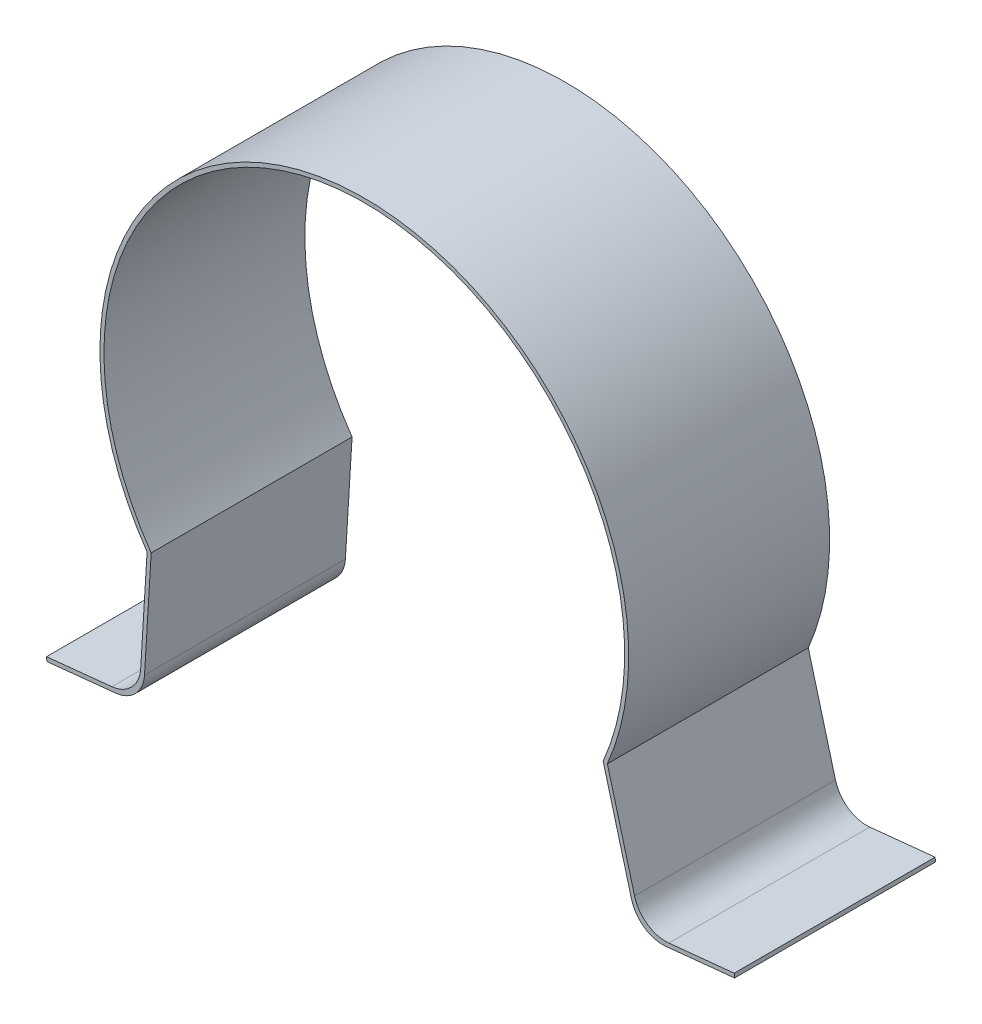
SolidWorks part; units mm, degrees
ref_plane "Спереди" through (0, 0, 0) normal (0, 0, 1) x (1, 0, 0)
ref_plane "Сверху" through (0, 0, 0) normal (0, 1, 0) x (1, 0, 0)
ref_plane "Справа" through (0, 0, 0) normal (1, 0, 0) x (0, 0, -1)
sketch "Эскиз8" plane through (0, 0, 0) normal (0, 0, 1) x (1, 0, 0)
  line L0 (-26.5227, -18.6093) -> (-27.5606, -35.5776)
  line L1 (-27.5606, -35.5776) -> (-39.4981, -36.8007)
  line L2 (0, 31.1118) -> (0, 49.2071) construction
  line L3 (34.1389, -29.3254) -> (46.0777, -28.1156)
  line L4 (29.7166, -12.9106) -> (34.1389, -29.3254)
  line L6 (46.0777, -28.1156) -> (-39.4841, -36.7858) construction
  arc A0 (29.7166, -12.9106) -> (-26.5227, -18.6093) centre (0, 0) ccw
  arc A1 (10.0641, 30.7973) -> (-18.6079, -26.5237) centre (0, 0) ccw construction
extrude "Вытянуть-Тонкостенный1" add sketch "Эскиз8" along normal blind 25 thin
fillet "Скругление1" radius 4 1 edges at (-28.0338, -35.1234, 12.5)
fillet "Скругление2" radius 4 1 edges at (-27.5606, -35.5776, 12.5)
fillet "Скругление3" radius 4 2 edges at (34.1389, -29.3254, 12.5) (34.5111, -28.7851, 12.5)
